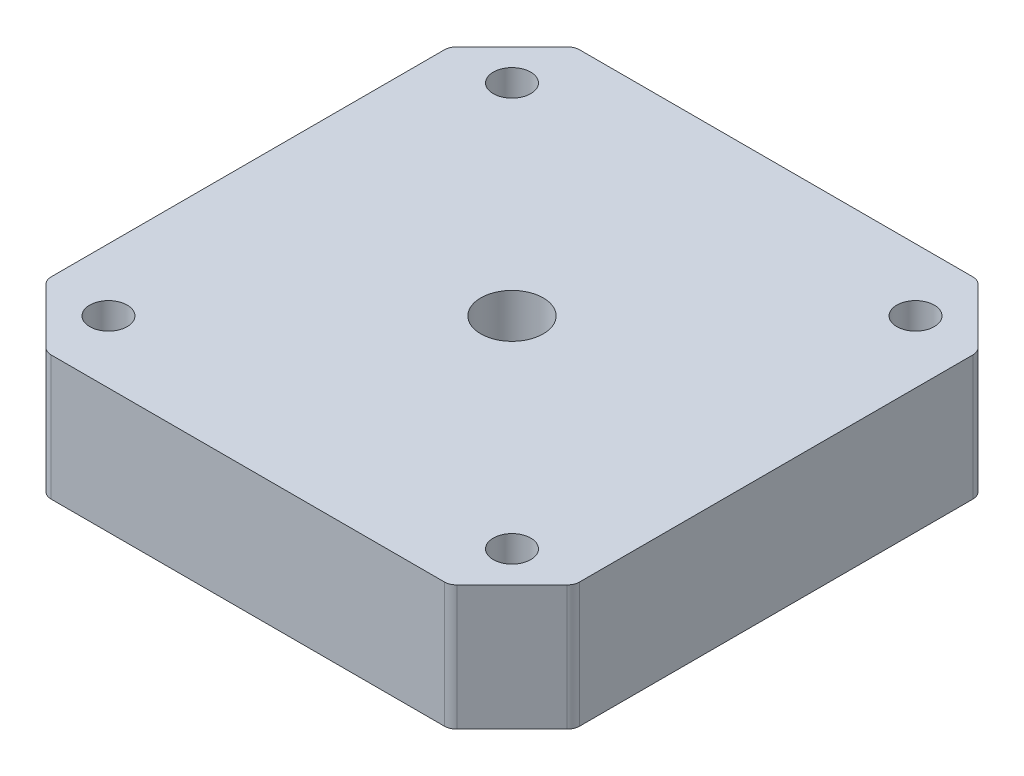
SolidWorks part; units mm, degrees
ref_plane "Front Plane" through (0, 0, 0) normal (0, 0, 1) x (1, 0, 0)
ref_plane "Top Plane" through (0, 0, 0) normal (0, 1, 0) x (1, 0, 0)
ref_plane "Right Plane" through (0, 0, 0) normal (1, 0, 0) x (0, 0, -1)
sketch "Sketch1" plane through (0, 0, 0) normal (0, 1, 0) x (1, 0, 0)
  line L0 (5, 42.3) -> (0, 37.3)
  line L1 (0, 0) -> (42.3, 0)
  line L2 (0, 0) -> (0, 42.3)
  line L3 (0, 42.3) -> (42.3, 42.3)
  line L4 (42.3, 0) -> (42.3, 42.3)
  line L5 (0, 5) -> (5, 0)
  line L6 (37.3, 42.3) -> (42.3, 37.3)
  line L7 (42.3, 5) -> (37.3, 0)
  circle A0 centre (5, 5) radius 1.5
  circle A1 centre (5, 37.3) radius 1.5
  circle A2 centre (37.3, 37.3) radius 1.5
  circle A3 centre (37.3, 5) radius 1.5
  dimension "D5" = 3
  dimension "D7" = 3
  dimension "D9" = 3
  dimension "D10" = 3
  dimension "D1" = 42.3
  dimension "D2" = 42.3
  dimension "D3" = 5
  dimension "D4" = 5
  dimension "D6" = 5
  dimension "D8" = 5
extrude "Boss-Extrude1" add sketch "Sketch1" along normal blind 10 contours L7 L4 L6 L3 L0 L2 L5 L1 A3 A2 A1 A0
fillet "Fillet1" radius 1 1 edges at (0, 5, -5)
fillet "Fillet2" radius 1 1 edges at (5, 5, 0)
fillet "Fillet3" radius 1 1 edges at (37.3, 5, 0)
fillet "Fillet4" radius 1 1 edges at (42.3, 5, -5)
fillet "Fillet5" radius 1 1 edges at (42.3, 5, -37.3)
fillet "Fillet6" radius 1 1 edges at (37.3, 5, -42.3)
fillet "Fillet7" radius 1 1 edges at (5, 5, -42.3)
fillet "Fillet8" radius 1 1 edges at (0, 5, -37.3)
sketch "Sketch2" plane through (0, 0, 0) normal (0, -1, 0) x (1, 0, 0)
  circle A0 centre (21.15, -21.15) radius 12.5
  dimension "D1" = 25
extrude "Boss-Extrude2" add sketch "Sketch2" along normal blind 2
sketch "Sketch4" plane through (0, -2, 0) normal (0, -1, 0) x (1, 0, 0)
  circle A0 centre (21.15, -21.15) radius 2.5
  dimension "D1" = 5
extrude "Cut-Extrude1" cut sketch "Sketch4" against normal blind 10
sketch "Sketch5" plane through (0, -2, 0) normal (0, -1, 0) x (1, 0, 0)
  circle A0 centre (21.15, -21.15) radius 2.5
extrude "Cut-Extrude2" cut sketch "Sketch5" against normal blind 50
